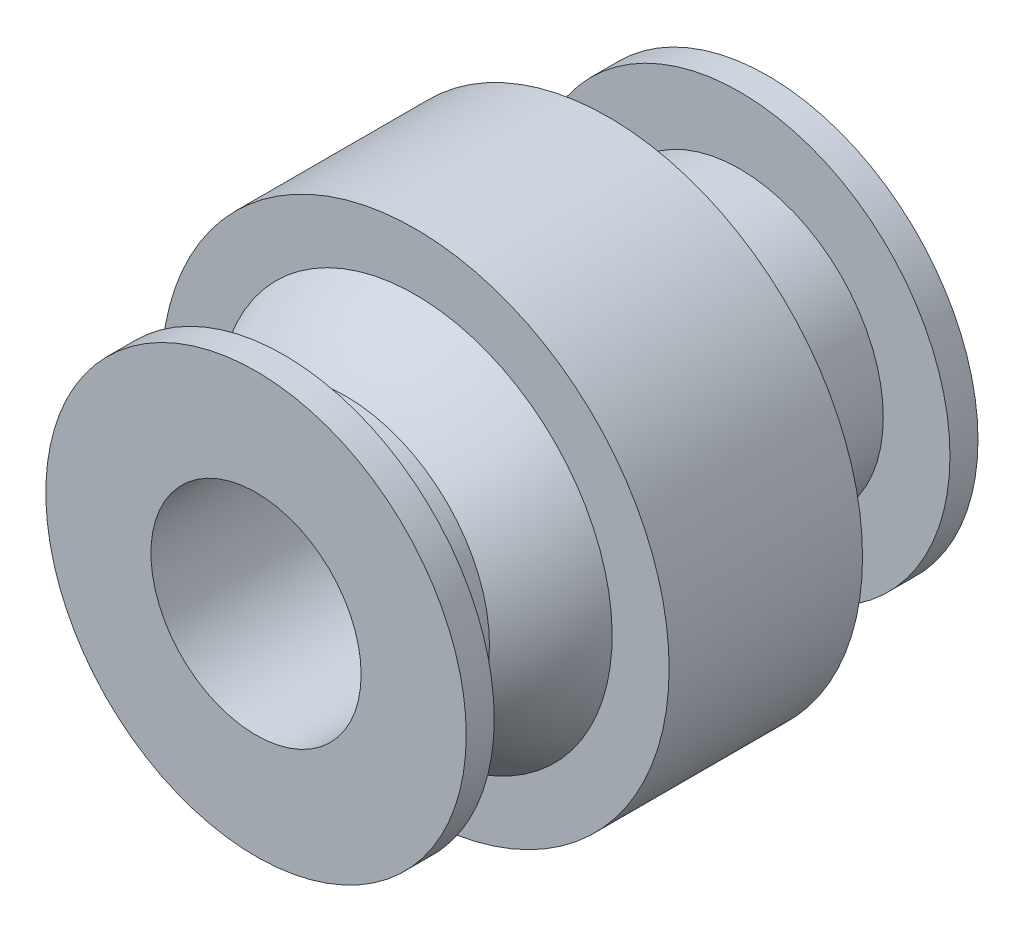
SolidWorks part; units mm, degrees
material "Alloy Steel"
ref_plane "X-Y Datum" through (0, 0, 0) normal (0, 0, 1) x (1, 0, 0)
ref_plane "X-Z Datum" through (0, 0, 0) normal (0, 1, 0) x (1, 0, 0)
ref_plane "Y-Z Datum" through (0, 0, 0) normal (1, 0, 0) x (0, 0, -1)
sketch "Sketch1" plane through (0, 0, 0) normal (1, 0, 0) x (0, 0, -1)
  line L0 (82.1362, -22.0492) -> (50082.1362, -22.0492) construction
  line L1 (71.12, -5.2479) -> (71.12, 49994.7521) construction
  line L2 (66.7385, -30.973) -> (71.12, -22.0492) construction
  line L3 (71.12, -22.0492) -> (63.6, -28.5516) construction
  line L4 (60.7949, -26.8117) -> (81.4451, -26.8117)
  line L5 (60.7949, -28.5516) -> (63.6, -28.5516)
  line L6 (66.7385, -30.973) -> (66.7385, -33.5554)
  line L7 (66.7385, -33.5554) -> (75.5015, -33.5554)
  line L8 (75.5015, -33.5554) -> (75.5015, -30.973)
  line L11 (78.64, -28.5516) -> (81.4451, -28.5516)
  line L28 (81.4451, -28.5516) -> (81.4451, -26.8117) construction
  line L31 (60.7949, -26.8117) -> (59.5249, -26.8117)
  line L32 (59.5249, -26.8117) -> (59.5249, -31.5742)
  line L33 (59.5249, -31.5742) -> (60.7949, -31.5742)
  line L34 (60.7949, -31.5742) -> (60.7949, -28.5516)
  line L35 (81.4451, -28.5516) -> (81.4451, -31.5742)
  line L36 (81.4451, -31.5742) -> (82.7151, -31.5742)
  line L37 (82.7151, -31.5742) -> (82.7151, -26.8117)
  line L38 (82.7151, -26.8117) -> (81.4451, -26.8117)
  arc A0 (63.6, -28.5516) -> (66.7385, -30.973) centre (71.12, -22.0492) ccw
  arc A1 (75.5015, -30.973) -> (78.64, -28.5516) centre (71.12, -22.0492) ccw
  point P8 (71.12, -26.8117)
  point P15 (71.12, -33.5554)
  dimension "D1" = 9.525
  dimension "D3" = 8.763
  dimension "D5" = 23
  dimension "D2" = 13.0048
  dimension "D4" = 20.6502
  dimension "D6" = 23.0124
  dimension "D7" = 1.27
  dimension "D8" = 1.27
  dimension "D9" = 19.05
  dimension "D10" = 19.05
revolve "Revolve1" add sketch "Sketch1" angle 360 about L0
